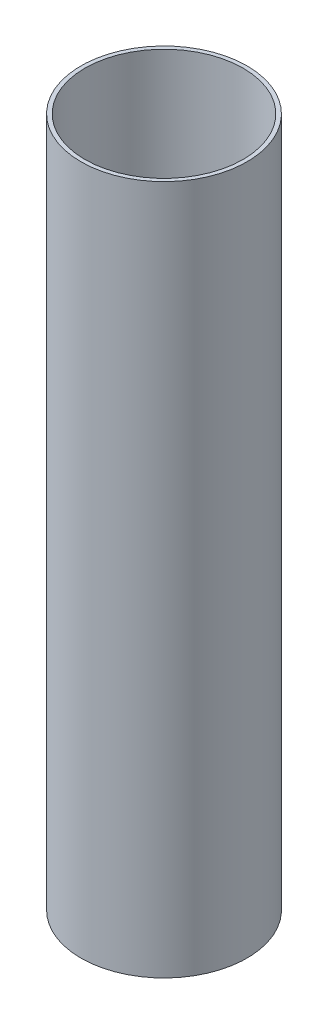
SolidWorks part; units mm, degrees
ref_plane "Front Plane" through (0, 0, 0) normal (0, 0, 1) x (1, 0, 0)
ref_plane "Top Plane" through (0, 0, 0) normal (0, 1, 0) x (1, 0, 0)
ref_plane "Right Plane" through (0, 0, 0) normal (1, 0, 0) x (0, 0, -1)
sketch "Sketch1" plane through (0, 0, 0) normal (0, 1, 0) x (1, 0, 0)
  circle A0 centre (0, 0) radius 6.3
  dimension "D1" = 12.6
extrude "Boss-Extrude1" add sketch "Sketch1" along normal blind 0.3
sketch "Sketch2" plane through (0, 0.3, 0) normal (0, 1, 0) x (1, 0, 0)
  circle A0 centre (0, 0) radius 6.3 construction
  circle A1 centre (0, 0) radius 6.3
  circle A2 centre (0, 0) radius 6
  dimension "D1" = 0.3
extrude "Boss-Extrude2" add sketch "Sketch2" along normal blind 52
